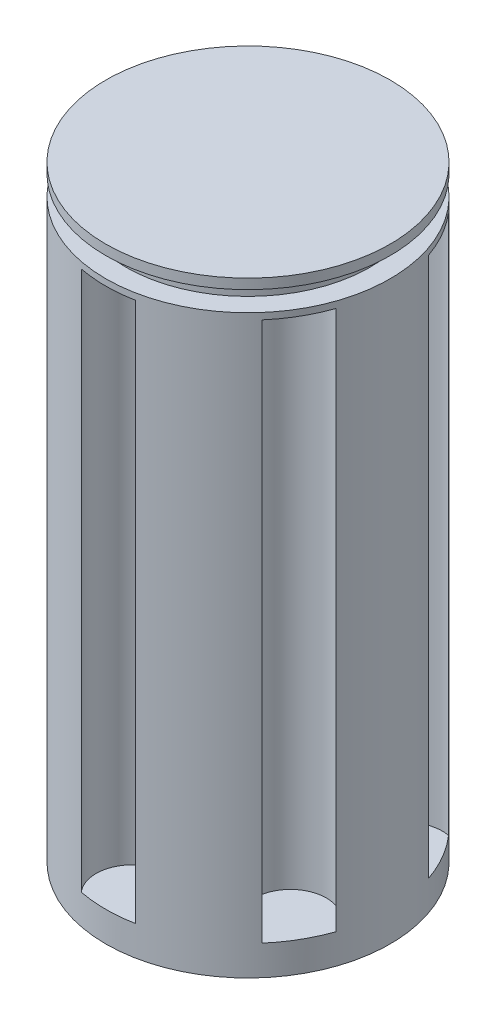
SolidWorks part; units mm, degrees
ref_plane "Front Plane" through (0, 0, 0) normal (0, 0, 1) x (1, 0, 0)
ref_plane "Top Plane" through (0, 0, 0) normal (0, 1, 0) x (1, 0, 0)
ref_plane "Right Plane" through (0, 0, 0) normal (1, 0, 0) x (0, 0, -1)
sketch "Sketch1" plane through (0, 0, 0) normal (0, 1, 0) x (1, 0, 0)
  arc A1 (-35.56, 0) -> (35.56, 0) centre (0, 0) cw
  arc A2 (-35.56, 0) -> (35.56, 0) centre (0, 0) ccw
  point P4 (0, 0)
  dimension "D1" = 35.56
extrude "Boss-Extrude1" add sketch "Sketch1" along normal blind 150
sketch "Sketch2" plane through (0, 0, 0) normal (0, -1, 0) x (-1, 0, 0)
  circle A0 centre (0, 0) radius 29 construction
  circle A1 centre (0, 29) radius 9
  circle A2 centre (0, 0) radius 29 construction
  circle A4 centre (0, 0) radius 29 construction
  circle A6 centre (0, 0) radius 29 construction
  circle A8 centre (0, 0) radius 29 construction
  circle A10 centre (0, 0) radius 29 construction
  circle A12 centre (0, -29) radius 9 [skipped]
  circle A13 centre (25.1147, -14.5) radius 9 [skipped]
  circle A14 centre (-25.1147, -14.5) radius 9 [skipped]
  circle A15 centre (-25.1147, 14.5) radius 9 [skipped]
  circle A16 centre (25.1147, 14.5) radius 9 [skipped]
  dimension "D1" = 58
  dimension "D2" = 18
  dimension "D3" = 6
extrude "Cut-Extrude7" cut sketch "Sketch2" against normal blind 135 from offset 7.5 offset against normal yes
pattern_circular "CirPattern1" count 6 over 360 about axis through (0, 0, 0) along (0, 1, 0) of "Cut-Extrude7"
sketch "Sketch3" plane through (0, 0, 0) normal (0, -1, 0) x (-1, 0, 0)
  circle A0 centre (0, 0) radius 19.05
  dimension "D1" = 38.1
extrude "Cut-Extrude8" cut sketch "Sketch3" against normal through all
sketch "Sketch5" plane through (0, 150, 0) normal (0, 1, 0) x (1, 0, 0)
  circle A0 centre (0, 0) radius 35.56
  circle A1 centre (0, 0) radius 35.56 construction
extrude "Cut-Extrude9" cut sketch "Sketch5" against normal offset from surface (5.9 mm away) 1.6 up to face at (-24.0582, 142.5, -13.89)
sketch "Sketch6" plane through (0, 144.1, 0) normal (0, 1, 0) x (1, 0, 0)
  circle A0 centre (0, 0) radius 30.56
  circle A1 centre (0, 0) radius 35.56 construction
  dimension "D1" = 5
extrude "Boss-Extrude2" add sketch "Sketch6" along normal blind 5
sketch "Sketch7" plane through (0, 149.1, 0) normal (0, 1, 0) x (1, 0, 0)
  circle A0 centre (0, 0) radius 35.56
  circle A1 centre (0, 0) radius 35.56 construction
extrude "Boss-Extrude3" add sketch "Sketch7" along normal blind 2.5
